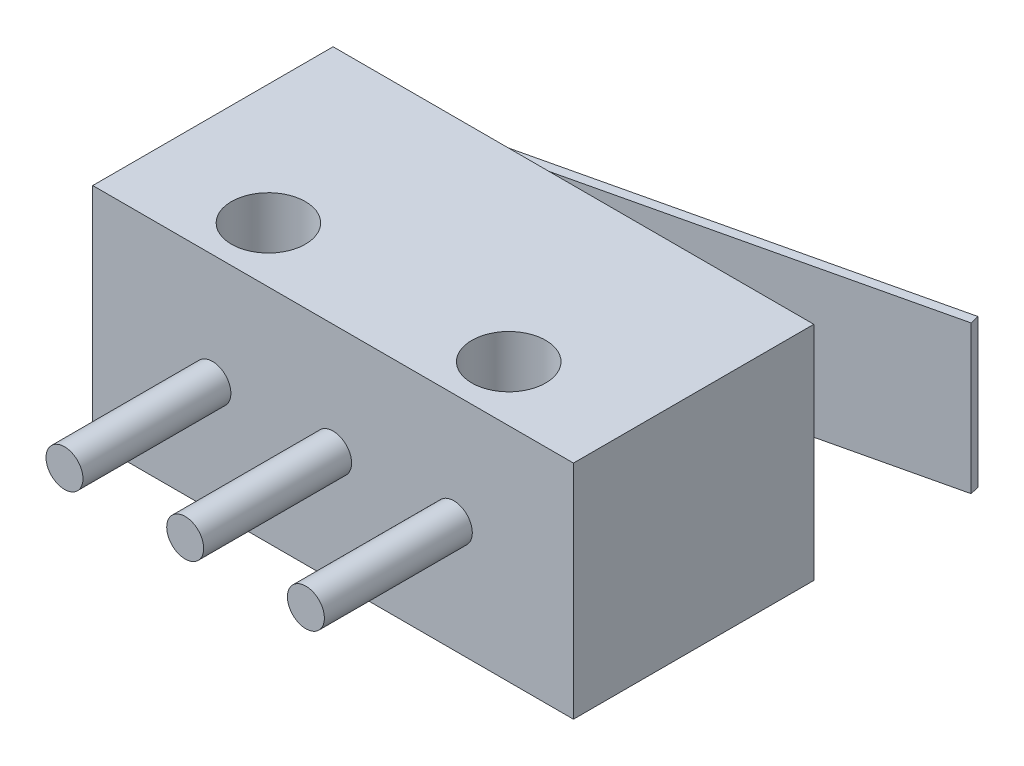
SolidWorks part; units mm, degrees
ref_plane "Спереди" through (0, 0, 0) normal (0, 0, 1) x (1, 0, 0)
ref_plane "Сверху" through (0, 0, 0) normal (0, 1, 0) x (1, 0, 0)
ref_plane "Справа" through (0, 0, 0) normal (1, 0, 0) x (0, 0, -1)
sketch "Эскиз1" plane through (0, 0, 0) normal (0, 1, 0) x (1, 0, 0)
  line L0 (6.5, -0.25) -> (1.5, -0.25) construction
  line L1 (6.5, -3.25) -> (-6.5, -3.25)
  line L2 (6.5, -3.25) -> (6.5, 3.25)
  line L3 (6.5, 3.25) -> (-6.5, 3.25)
  line L4 (-6.5, -3.25) -> (-6.5, 3.25)
  line L5 (6.5, -3.25) -> (-6.5, 3.25) construction
  line L6 (6.5, 3.25) -> (-6.5, -3.25) construction
  line L7 (1.5, -0.25) -> (1.5, -3.25) construction
  line L8 (4.25, -1.75) -> (6.5, -1.75) construction
  line L9 (0, 3.25) -> (0, 0) construction
  line L10 (4.25, -1.75) -> (3.25, -1.75) construction
  line L11 (3.25, -1.75) -> (3.25, -3.25) construction
  line L12 (-3.25, -1.75) -> (3.25, -1.75) construction
  circle A0 centre (3.25, -1.75) radius 1
  circle A1 centre (-3.25, -1.75) radius 1
  point P0 (0, 0)
  dimension "D5" = 2
  dimension "D1" = 13
  dimension "D2" = 6.5
  dimension "D3" = 5
  dimension "D4" = 3
  dimension "D6" = 1.5
  dimension "D7" = 6.5
extrude "Бобышка-Вытянуть1" add sketch "Эскиз1" along normal mid plane 6
sketch "Эскиз2" plane through (0, 0, 3.25) normal (0, 0, 1) x (1, 0, 0)
  line L0 (-6.5, 0) -> (6.5, 0) construction
  line L1 (-6.5, 3) -> (-6.5, -3) construction
  line L2 (6.5, 3) -> (6.5, -3) construction
  line L3 (0, 3) -> (0, 0) construction
  line L4 (-6.5, 3) -> (6.5, 3) construction
  circle A0 centre (-3.2642, 0) radius 0.5
  circle A1 centre (0, 0) radius 0.5
  circle A2 centre (3.2642, 0) radius 0.5
  dimension "D1" = 1
  dimension "D2" = 1
extrude "Бобышка-Вытянуть2" add sketch "Эскиз2" along normal blind 4
sketch "Эскиз3" plane through (0, 0, 0) normal (0, 1, 0) x (1, 0, 0)
  line L0 (-6.5, 3.25) -> (7.5662, 6.5305)
extrude "Вытянуть-Тонкостенный1" add sketch "Эскиз3" along normal mid plane 4 thin thin type mid plane wall 0.25
